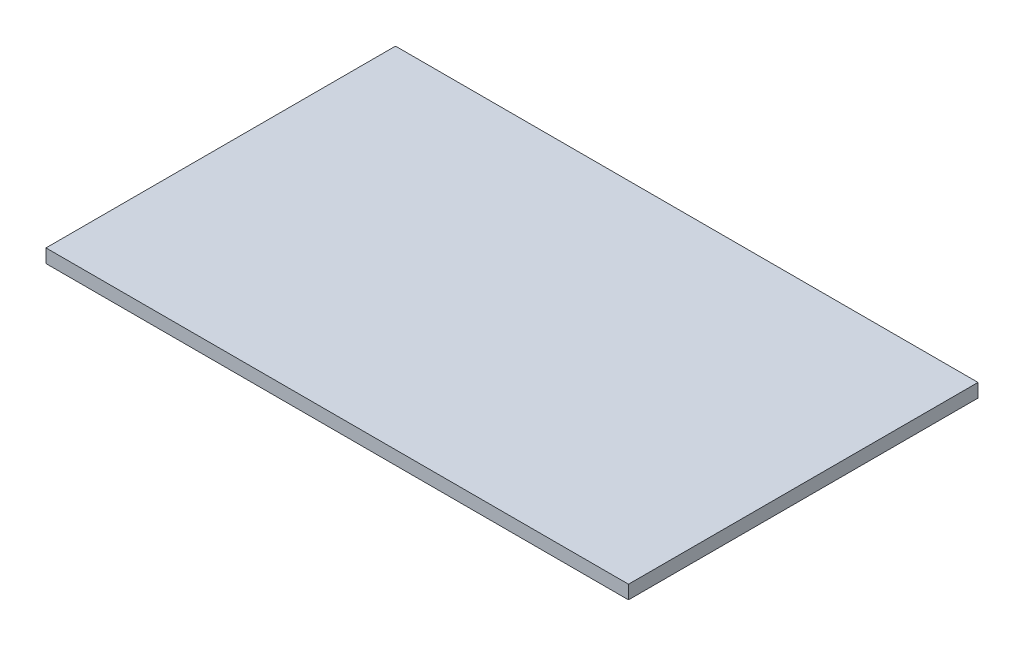
SolidWorks part; units mm, degrees
ref_plane "Front Plane" through (0, 0, 0) normal (0, 0, 1) x (1, 0, 0)
ref_plane "Top Plane" through (0, 0, 0) normal (0, 1, 0) x (1, 0, 0)
ref_plane "Right Plane" through (0, 0, 0) normal (1, 0, 0) x (0, 0, -1)
sketch "Sketch1" plane through (0, 0, 0) normal (0, 1, 0) x (1, 0, 0)
  line L1 (-63.9379, 42.0063) -> (236.0621, 42.0063)
  line L2 (-63.9379, 42.0063) -> (-63.9379, -137.9937)
  line L3 (-63.9379, -137.9937) -> (236.0621, -137.9937)
  line L4 (236.0621, 42.0063) -> (236.0621, -137.9937)
  dimension "D1" = 300
  dimension "D2" = 180
extrude "Boss-Extrude1" add sketch "Sketch1" along normal blind 7
